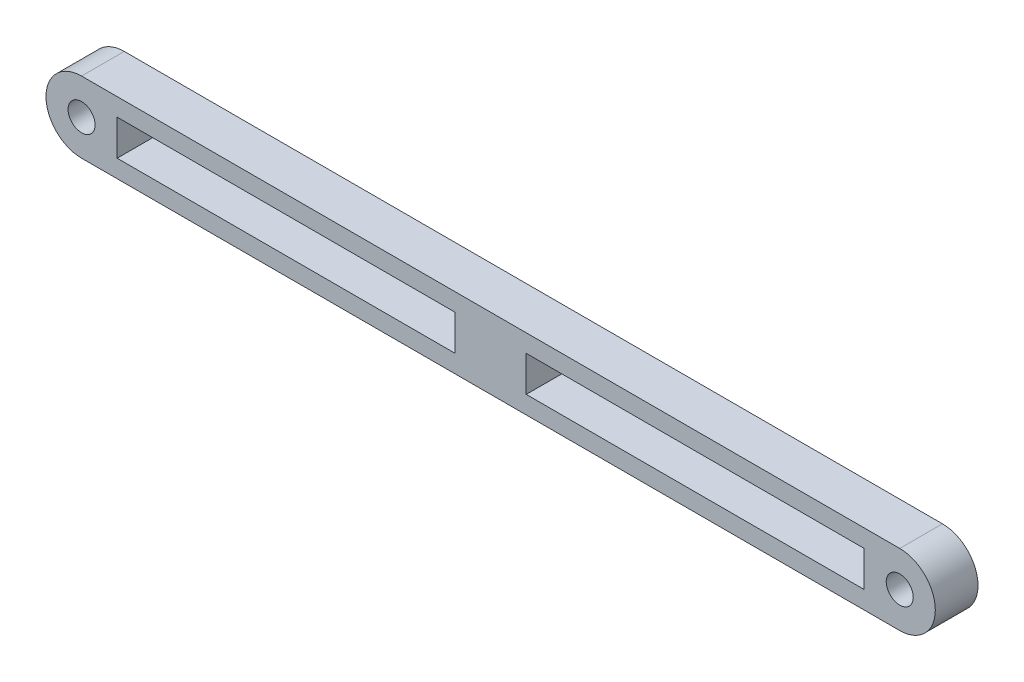
SolidWorks part; units mm, degrees
material "MDF"
ref_plane "Front Plane" through (0, 0, 0) normal (0, 0, 1) x (1, 0, 0)
ref_plane "Top Plane" through (0, 0, 0) normal (0, 1, 0) x (1, 0, 0)
ref_plane "Right Plane" through (0, 0, 0) normal (1, 0, 0) x (0, 0, -1)
sketch "Sketch1" plane through (0, 0, 0) normal (0, 0, 1) x (1, 0, 0)
  line L0 (0, -5) -> (0, 5) construction
  line L1 (-57.5, 5) -> (57.5, 5)
  line L2 (-57.5, -5) -> (57.5, -5)
  line L3 (57.5, 0) -> (-57.5, 0) construction
  arc A0 (57.5, 5) -> (57.5, -5) centre (57.5, 0) cw
  arc A1 (-57.5, 5) -> (-57.5, -5) centre (-57.5, 0) ccw
  circle A2 centre (-57.5, 0) radius 1.9
  circle A3 centre (57.5, 0) radius 1.9
  point P4 (0, 0)
  point P8 (0, 5)
  point P11 (0, -5)
  point P13 (0, 0)
  dimension "D3" = 3.8
  dimension "D4" = 3.8
  dimension "D1" = 10
  dimension "D2" = 115
extrude "Boss-Extrude1" add sketch "Sketch1" along normal blind 6
sketch "Sketch2" plane through (0, 0, 6) normal (0, 0, 1) x (1, 0, 0)
  line L0 (28.75, 0) -> (-28.75, 0) construction
  line L1 (-57.5, 1.9) -> (-57.5, -1.9) construction
  line L2 (-52.5, -2.5) -> (-5, -2.5)
  line L3 (-52.5, -2.5) -> (-52.5, 2.5)
  line L4 (-52.5, 2.5) -> (-5, 2.5)
  line L5 (-5, -2.5) -> (-5, 2.5)
  line L6 (-52.5, -2.5) -> (-5, 2.5) construction
  line L7 (-52.5, 2.5) -> (-5, -2.5) construction
  line L8 (5, -2.5) -> (52.5, -2.5)
  line L9 (5, -2.5) -> (5, 2.5)
  line L10 (5, 2.5) -> (52.5, 2.5)
  line L11 (52.5, -2.5) -> (52.5, 2.5)
  line L12 (5, -2.5) -> (52.5, 2.5) construction
  line L13 (5, 2.5) -> (52.5, -2.5) construction
  line L14 (57.5, 1.9) -> (57.5, -1.9) construction
  circle A0 centre (-57.5, 0) radius 1.9 construction
  circle A1 centre (57.5, 0) radius 1.9 construction
  point P4 (0, 0)
  point P22 (37.5, 0)
  dimension "D1" = 5
  dimension "D2" = 5
  dimension "D3" = 10
  dimension "D4" = 5
  dimension "D5" = 5
extrude "Cut-Extrude1" cut sketch "Sketch2" against normal through all
